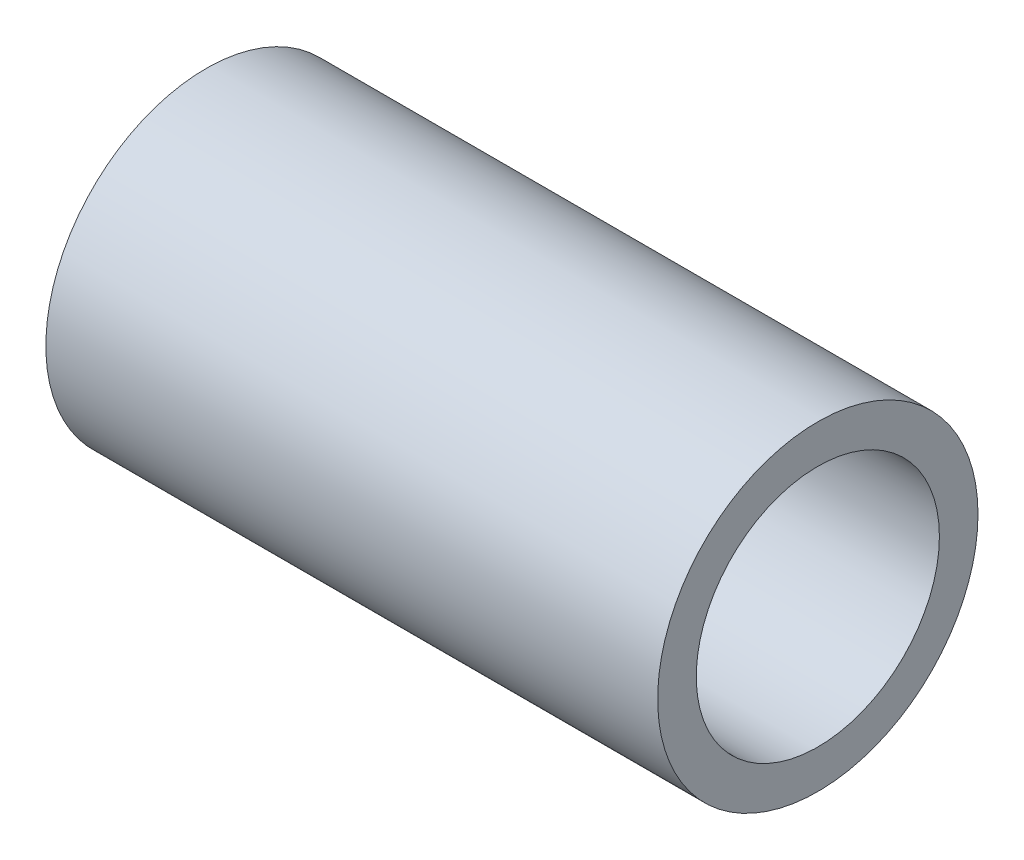
SolidWorks part; units mm, degrees
material "6061-T6 (SS)"
ref_plane "Front Plane" through (0, 0, 0) normal (0, 0, 1) x (1, 0, 0)
ref_plane "Top Plane" through (0, 0, 0) normal (0, 1, 0) x (1, 0, 0)
ref_plane "Right Plane" through (0, 0, 0) normal (1, 0, 0) x (0, 0, -1)
sketch "Sketch1" plane through (0, 0, 0) normal (1, 0, 0) x (0, 0, -1)
  circle A0 centre (0, 0) radius 10
  circle A1 centre (0, 0) radius 13.175
  dimension "D1" = 20
  dimension "D2" = 3.175
extrude "Extrude1" add sketch "Sketch1" along normal blind 50.325
